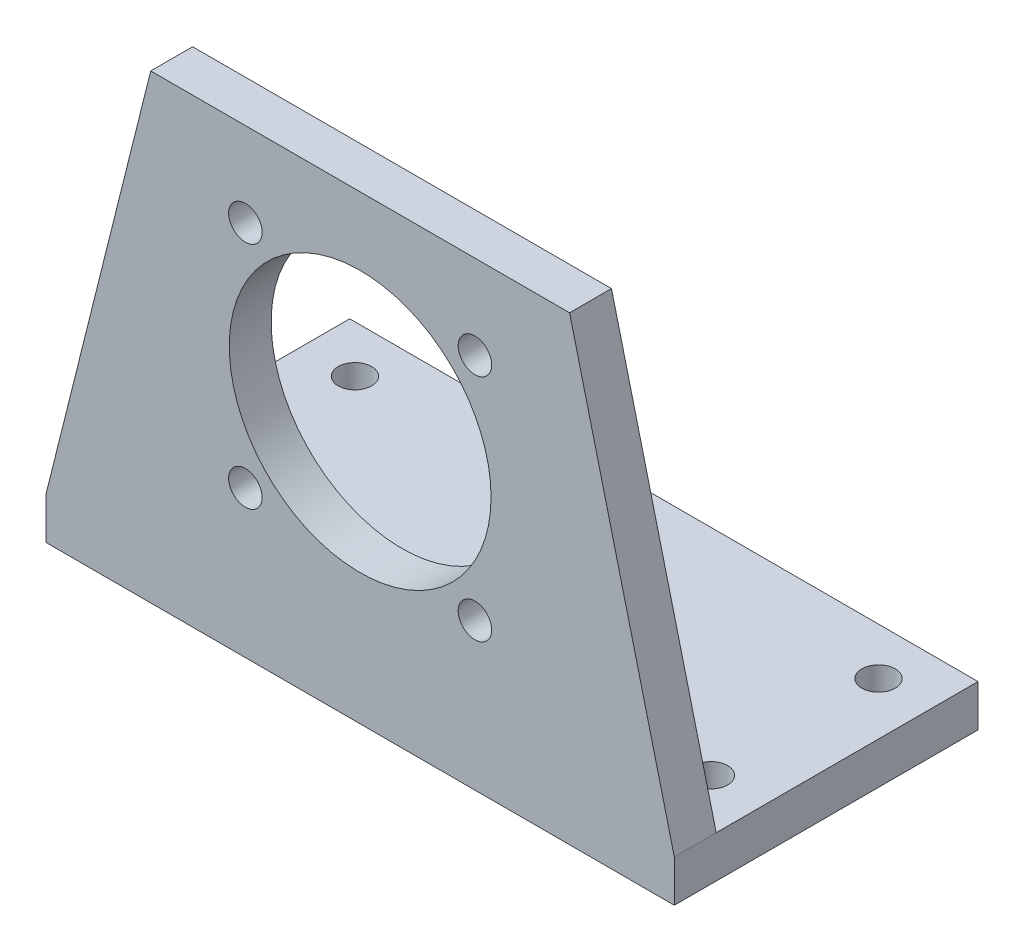
SolidWorks part; units mm, degrees
ref_plane "前视基准面" through (0, 0, 0) normal (0, 0, 1) x (1, 0, 0)
ref_plane "上视基准面" through (0, 0, 0) normal (0, 1, 0) x (1, 0, 0)
ref_plane "右视基准面" through (0, 0, 0) normal (1, 0, 0) x (0, 0, -1)
sketch "草图2" plane through (0, 0, 0) normal (0, 0, 1) x (1, 0, 0)
  line L0 (-26.7881, -21) -> (33.2119, -21)
  line L1 (33.2119, -21) -> (23.2119, 19)
  line L2 (23.2119, 19) -> (-16.7881, 19)
  line L3 (-16.7881, 19) -> (-26.7881, -21)
  line L4 (-26.7881, -21) -> (33.2119, -21)
  line L5 (33.2119, -21) -> (33.2119, -25)
  line L6 (33.2119, -25) -> (-26.7881, -25)
  line L7 (-26.7881, -25) -> (-26.7881, -21)
  line L8 (3.2119, 22) -> (3.2119, -28) construction
  line L9 (-12.7881, 0) -> (19.2119, 0) construction
  line L10 (16.647, 13.435) -> (11.6972, 8.4853) construction
  line L11 (-5.2733, -8.4853) -> (-10.2231, -13.435) construction
  line L12 (-10.2231, 13.435) -> (-5.2733, 8.4853) construction
  line L13 (11.6972, -8.4853) -> (16.647, -13.435) construction
  circle A0 centre (3.2119, 0) radius 15.5 construction
  circle A1 centre (14.1721, 10.9602) radius 1.6
  circle A2 centre (3.2119, 0) radius 12.5
  circle A3 centre (-7.7482, 10.9602) radius 1.6
  circle A4 centre (-7.7482, -10.9602) radius 1.6
  circle A5 centre (14.1721, -10.9602) radius 1.6
extrude "凸台-拉伸1" add sketch "草图2" along normal blind 4 contours L2 L3 L0 L1 A5 A4 A3 A2 A1 | L7 L6 L5 L0
sketch "草图3" plane through (0, 0, 0) normal (0, 0, -1) x (-1, 0, 0)
  line L1 (-33.2119, -21) -> (26.7881, -21)
  line L2 (-33.2119, -21) -> (-33.2119, -25)
  line L3 (-33.2119, -25) -> (26.7881, -25)
  line L4 (26.7881, -21) -> (26.7881, -25)
extrude "凸台-拉伸2" add sketch "草图3" along normal blind 25
sketch "草图4" plane through (0, -25, 0) normal (0, -1, 0) x (1, 0, 0)
  line L0 (33.2119, 4) -> (-26.7881, 4) construction
  line L1 (-21.7881, -4.5) -> (28.2119, -4.5) construction
  line L2 (-21.7881, -4.5) -> (-21.7881, -20.5) construction
  line L3 (-21.7881, -20.5) -> (28.2119, -20.5) construction
  line L4 (28.2119, -4.5) -> (28.2119, -20.5) construction
  line L5 (-26.7881, 4) -> (-26.7881, -25) construction
  line L6 (33.2119, 4) -> (33.2119, -25) construction
  circle A0 centre (-21.7881, -4.5) radius 1.6
  circle A1 centre (28.2119, -4.5) radius 1.6
  circle A2 centre (28.2119, -20.5) radius 1.6
  circle A3 centre (-21.7881, -20.5) radius 1.6
  dimension "D5" = 3.2
  dimension "D1" = 8.5
  dimension "D2" = 5
  dimension "D3" = 5
  dimension "D4" = 16
extrude "切除-拉伸1" cut sketch "草图4" against normal blind 25
